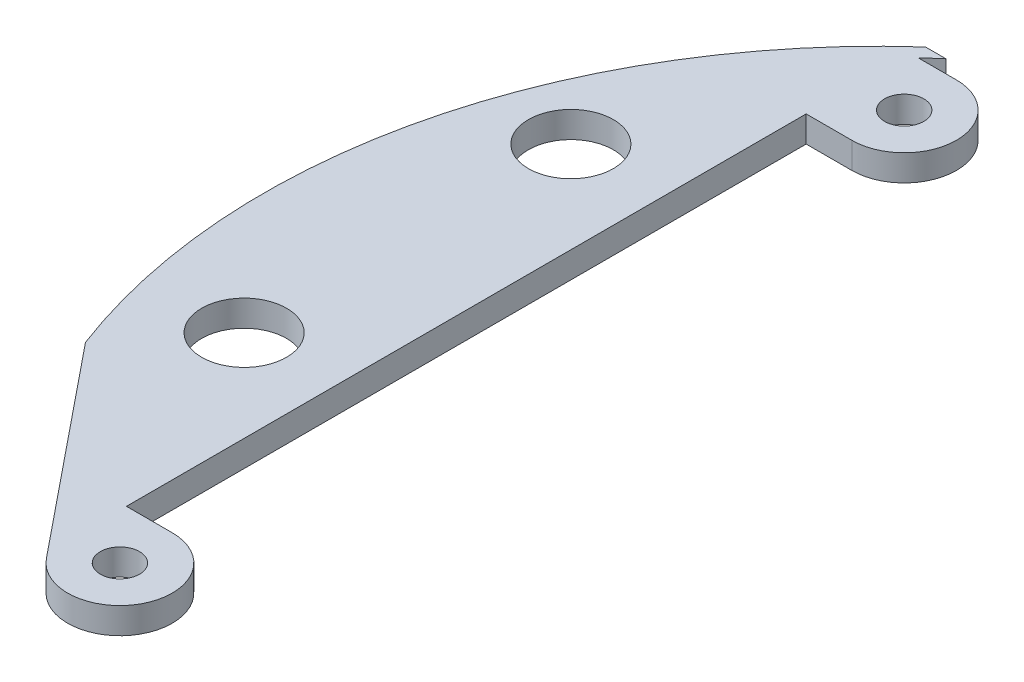
SolidWorks part; units mm, degrees
ref_plane "Спереди" through (0, 0, 0) normal (0, 0, 1) x (1, 0, 0)
ref_plane "Сверху" through (0, 0, 0) normal (0, 1, 0) x (1, 0, 0)
ref_plane "Справа" through (0, 0, 0) normal (1, 0, 0) x (0, 0, -1)
sketch "Эскиз1" plane through (0, 0, 0) normal (0, 1, 0) x (1, 0, 0)
  line L1 (-3, -26) -> (3, -26)
  line L2 (-3, -26) -> (-3, 26)
  line L3 (-3, 26) -> (3, 26)
  line L4 (3, -26) -> (3, 26)
  line L5 (-3, -26) -> (3, 26) construction
  line L6 (-3, 26) -> (3, -26) construction
  line L7 (-10, -35) -> (10, -35)
  line L8 (-10, -35) -> (-10, 35)
  line L9 (-10, 35) -> (10, 35)
  line L10 (10, -35) -> (10, 35)
  line L11 (-10, -35) -> (10, 35) construction
  line L12 (-10, 35) -> (10, -35) construction
  circle A0 centre (0, 30) radius 1.5
  circle A1 centre (0, -30) radius 1.5
  point P4 (0, 0)
  point P6 (0, 0)
  dimension "D2" = 3
  dimension "D1" = 60
  dimension "D3" = 30
  dimension "D4" = 52
  dimension "D5" = 6
  dimension "D6" = 20
  dimension "D7" = 70
extrude "Бобышка-Вытянуть1" add sketch "Эскиз1" along normal blind 2
sketch "Эскиз2" plane through (0, 2, 0) normal (0, 1, 0) x (1, 0, 0)
  line L0 (3, 26) -> (-3, 26) construction
  line L1 (3, 26) -> (-3.5, 26)
  line L2 (60.5, -32.5) -> (60.5, 32.5)
  line L3 (-4.5, 32.5) -> (-4.5, -32.5)
  line L4 (10, -35) -> (10, 35)
  line L5 (10, 35) -> (-10, 35)
  line L6 (-10, 35) -> (-10, -35)
  line L7 (-10, -35) -> (10, -35)
  line L8 (10, -35) -> (10, 35)
  line L9 (10, 35) -> (-10, 35)
  line L10 (-10, 35) -> (-10, -35)
  line L11 (-10, -35) -> (10, -35)
  line L12 (60.5, -32.5) -> (60.5, 32.5)
  line L13 (-4.5, 32.5) -> (-4.5, -32.5)
  line L14 (-1000, 0) -> (49000, 0) construction
  line L15 (-3.5, -28.0635) -> (-3.5, 28.0635)
  line L16 (-3, 26) -> (-3, -26) construction
  line L17 (0, 34) -> (-4.45, 34)
  line L18 (0, -26) -> (-3.5, -26)
  line L19 (-15.9316, -16.7037) -> (-3.1069, -32.5193)
  circle A0 centre (0, 30) radius 4
  circle A1 centre (0, -30) radius 4
  arc A2 (-4.5, -32.5) -> (60.5, -32.5) centre (28, -0.1296) ccw
  arc A3 (60.5, 32.5) -> (-4.5, 32.5) centre (28, 0.1296) ccw
  arc A4 (-4.5, -32.5) -> (60.5, -32.5) centre (28, -0.1296) ccw
  arc A5 (60.5, 32.5) -> (-4.5, 32.5) centre (28, 0.1296) ccw
  arc A6 (20.5, 46.3977) -> (-15.9316, -16.7037) centre (28, 0) ccw construction
  arc A7 (20.5, 46.3977) -> (-15.9316, -16.7037) centre (28, 0) ccw
  line M20 (10, -35) -> (10, 35)
  line M21 (10, 35) -> (-10, 35)
  line M22 (-10, 35) -> (-10, -35)
  line M23 (-10, -35) -> (10, -35)
  line M24 (3, 26) -> (3, -26)
  line M25 (3, -26) -> (-3, -26)
  line M26 (-3, -26) -> (-3, 26)
  dimension "D3" = 0.5
  dimension "D1" = 0
  dimension "D2" = 0
extrude "Вырез-Вытянуть1" cut sketch "Эскиз2" against normal through all contours L14 L15 L18 M26 | L15 L14 L1 M26 | L14 L8 A5 L17 A0 L1 M24 M21 | A7 M21 M22 | L14 A1 L19 L13 A4 L11 M24 M25 M20 | A4 L13 L19 L10 M23
sketch "Эскиз3" plane through (0, 2, 0) normal (0, 1, 0) x (1, 0, 0)
  line L7 (-3.5, -26) -> (-3.5, 26)
  line L8 (0, 34) -> (-2.9336, 34)
  line L9 (-10, 27.6586) -> (-10, -24.0187)
  line L10 (-10, -24.0187) -> (-3.1069, -32.5193)
  line L11 (0, -26) -> (-3.5, -26)
  line L12 (-3.5, -26) -> (-3.5, 26)
  line L15 (-3.5, 26) -> (0, 26)
  line L16 (0, 34) -> (-2.9336, 34)
  line L17 (-10, 27.6586) -> (-10, -24.0187)
  line L18 (-15.9316, -16.7037) -> (-3.1069, -32.5193)
  line L19 (0, -26) -> (-3.5, -26)
  line L23 (-3.5, 26) -> (0, 26)
  line L28 (-1.8018, 35) -> (-3.3688, 35)
  line L29 (-1.8018, 35) -> (-3.3688, 35)
  arc A0 (20.5, 46.3977) -> (-15.9316, -16.7037) centre (28, 0) ccw construction
  arc A1 (20.5, 46.3977) -> (-15.9316, -16.7037) centre (28, 0) ccw
  arc A5 (0, 26) -> (0, 34) centre (0, 30) ccw
  arc A6 (-1.8018, 35) -> (-2.9336, 34) centre (28, 0.1296) ccw
  arc A7 (-3.1069, -32.5193) -> (0, -26) centre (0, -30) ccw
  arc A8 (0, 26) -> (0, 34) centre (0, 30) ccw
  arc A10 (-3.1069, -32.5193) -> (0, -26) centre (0, -30) ccw
  arc A11 (-1.8018, 35) -> (-2.9336, 34) centre (28, 0.1296) ccw
  arc A13 (-3.3688, 35) -> (-10, 27.6586) centre (28, 0) ccw
  arc A14 (-3.3688, 35) -> (-10, 27.6586) centre (28, 0) ccw
  line M17 (-10, 27.6586) -> (-10, -24.0187)
  dimension "D1" = 0
extrude "Бобышка-Вытянуть3" add sketch "Эскиз3" against normal blind 2 contours A1 L18 M17
sketch "Эскиз4" plane through (0, 2, 0) normal (0, 1, 0) x (1, 0, 0)
  line L0 (-3.5, -26) -> (-3.5, 26) construction
  circle A0 centre (-10.5, 15) radius 3.25
  circle A1 centre (-10.5, -10) radius 3.25
  point P4 (-11.0011, -1.3969)
  point P5 (0, 0)
  point P6 (-11.0011, 16.0174)
  point P9 (-10.5, -9)
  point P11 (-7.3565, 19.2225)
  dimension "D1" = 6.5
  dimension "D2" = 7
  dimension "D3" = 25
  dimension "D4" = 15
extrude "Вырез-Вытянуть2" cut sketch "Эскиз4" against normal through all
